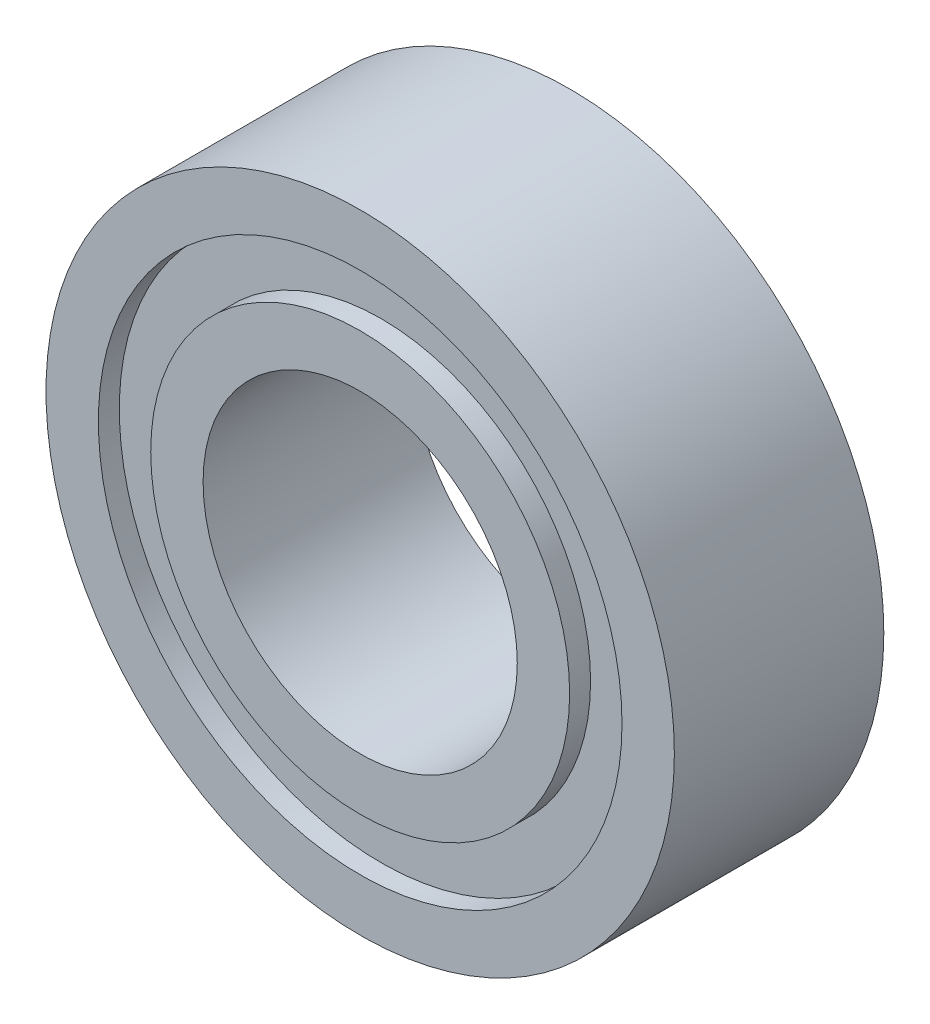
SolidWorks part; units mm, degrees
ref_plane "Front Plane" through (0, 0, 0) normal (0, 0, 1) x (1, 0, 0)
ref_plane "Top Plane" through (0, 0, 0) normal (0, 1, 0) x (1, 0, 0)
ref_plane "Right Plane" through (0, 0, 0) normal (1, 0, 0) x (0, 0, -1)
sketch "Sketch2" plane through (0, 0, 0) normal (0, 0, 1) x (1, 0, 0)
  circle A0 centre (0, 0) radius 2.3813
  circle A1 centre (0, 0) radius 4.7625
  dimension "D1" = 4.7625
  dimension "D2" = 9.525
extrude "Boss-Extrude1" add sketch "Sketch2" along normal blind 3.175
sketch "Sketch3" plane through (0, 0, 3.175) normal (0, 0, 1) x (1, 0, 0)
  circle A0 centre (0, 0) radius 3.175
  circle A1 centre (0, 0) radius 3.9688
  dimension "D1" = 6.35
  dimension "D2" = 7.9375
extrude "Cut-Extrude1" cut sketch "Sketch3" against normal blind 0.3175
sketch "Sketch4" plane through (0, 0, 0) normal (0, 0, -1) x (-1, 0, 0)
  circle A0 centre (0, 0) radius 3.175 construction
  circle A1 centre (0, 0) radius 3.9688 construction
  circle A2 centre (0, 0) radius 3.175
  circle A3 centre (0, 0) radius 3.9688
extrude "Cut-Extrude2" cut sketch "Sketch4" against normal blind 0.635
